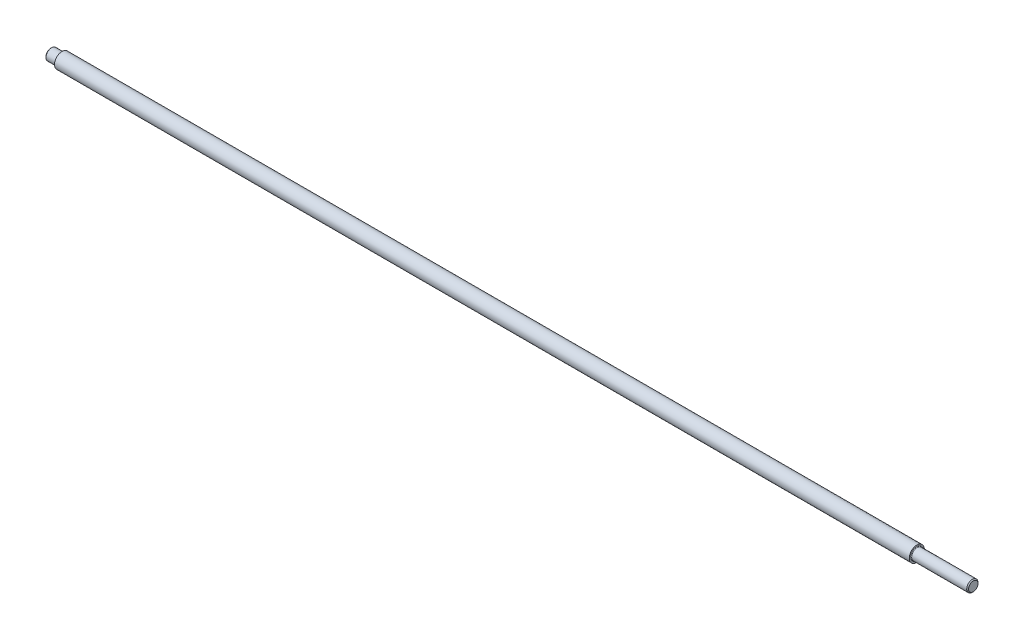
SolidWorks part; units mm, degrees
ref_plane "Front Plane" through (0, 0, 0) normal (0, 0, 1) x (1, 0, 0)
ref_plane "Top Plane" through (0, 0, 0) normal (0, 1, 0) x (1, 0, 0)
ref_plane "Right Plane" through (0, 0, 0) normal (1, 0, 0) x (0, 0, -1)
sketch "Sketch1" plane through (0, 0, 0) normal (0, 0, 1) x (1, 0, 0)
  line L0 (0, 2.5) -> (0, 0)
  line L1 (0, 0) -> (490, 0)
  line L2 (490, 0) -> (490, 2.5)
  line L3 (490, 2.5) -> (489.5, 3)
  line L4 (489.5, 3) -> (460.3, 3)
  line L5 (460, 3.3) -> (460, 4)
  line L6 (460, 4) -> (6, 4)
  line L7 (6, 4) -> (6, 3.3)
  line L8 (5.7, 3) -> (0.5, 3)
  line L9 (0.5, 3) -> (0, 2.5)
  line L10 (0, 0) -> (490, 0) construction
  arc A0 (460.3, 3) -> (460, 3.3) centre (460.3, 3.3) cw
  arc A1 (6, 3.3) -> (5.7, 3) centre (5.7, 3.3) cw
revolve "Revolve1" add sketch "Sketch1" angle 360 about L10
